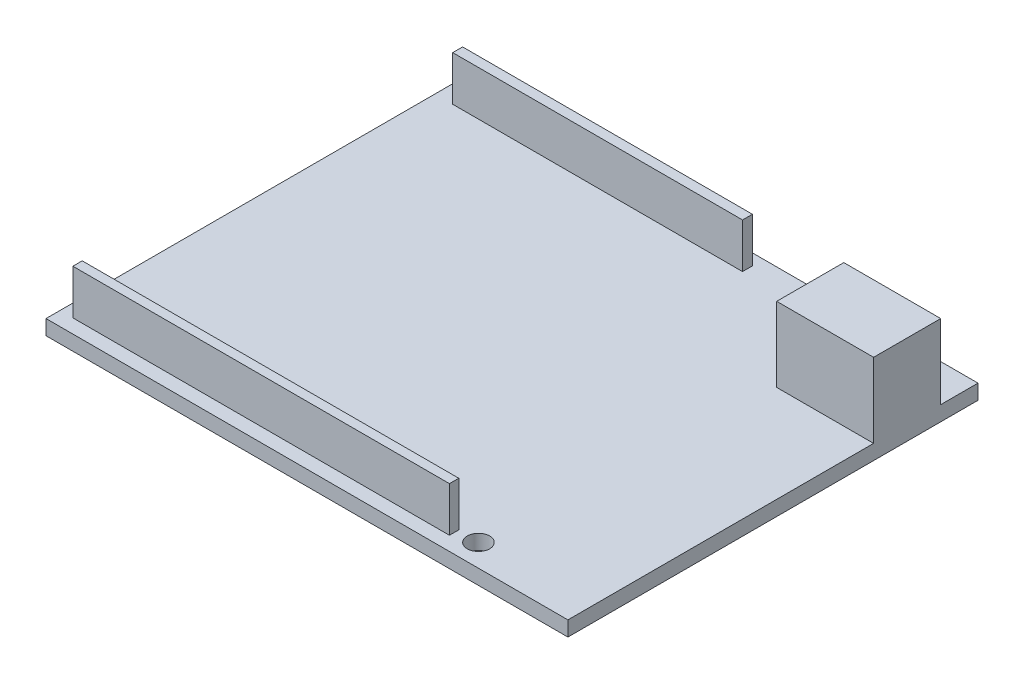
SolidWorks part; units mm, degrees
ref_plane "Plan de face" through (0, 0, 0) normal (0, 0, 1) x (1, 0, 0)
ref_plane "Plan de dessus" through (0, 0, 0) normal (0, 1, 0) x (1, 0, 0)
ref_plane "Plan de droite" through (0, 0, 0) normal (1, 0, 0) x (0, 0, -1)
sketch "Esquisse2" plane through (0, 0, 0) normal (0, 1, 0) x (1, 0, 0)
  line L1 (-35, 27.5) -> (35, 27.5)
  line L2 (-35, 27.5) -> (-35, -27.5)
  line L3 (-35, -27.5) -> (35, -27.5)
  line L4 (35, 27.5) -> (35, -27.5)
  line L5 (-35, 27.5) -> (35, -27.5) construction
  line L6 (-35, -27.5) -> (35, 27.5) construction
  point P0 (0, 0)
  dimension "D1" = 70
  dimension "D2" = 55
extrude "Boss.-Extru.1" add sketch "Esquisse2" along normal blind 2
sketch "Esquisse3" plane through (0, 2, 0) normal (0, 1, 0) x (1, 0, 0)
  line L0 (35, -27.5) -> (35, -12.5) construction
  line L1 (35, -27.5) -> (35, 27.5) construction
  line L2 (35, 27.5) -> (35, 22.5) construction
  line L4 (35, 22.5) -> (22, 22.5)
  line L5 (35, 22.5) -> (35, 13.5)
  line L6 (35, 13.5) -> (22, 13.5)
  line L7 (22, 22.5) -> (22, 13.5)
  dimension "D1" = 15
  dimension "D2" = 5
  dimension "D3" = 9
  dimension "D4" = 13
extrude "Boss.-Extru.2" add sketch "Esquisse3" along normal blind 10
sketch "Esquisse4" plane through (0, 2, 0) normal (0, 1, 0) x (1, 0, 0)
  line L1 (-32.6136, 25.9878) -> (6.2577, 25.9878)
  line L2 (-32.6136, 25.9878) -> (-32.6136, 24.6626)
  line L3 (-32.6136, 24.6626) -> (6.2577, 24.6626)
  line L4 (6.2577, 25.9878) -> (6.2577, 24.6626)
  line L5 (-33.2762, -24.3682) -> (17.227, -24.3682)
  line L6 (-33.2762, -24.3682) -> (-33.2762, -25.6197)
  line L7 (-33.2762, -25.6197) -> (17.227, -25.6197)
  line L8 (17.227, -24.3682) -> (17.227, -25.6197)
extrude "Boss.-Extru.3" add sketch "Esquisse4" along normal blind 6
sketch "Esquisse5" plane through (0, 2, 0) normal (0, 1, 0) x (1, 0, 0)
  line L0 (35, -27.5) -> (20, -27.5) construction
  line L1 (-35, -27.5) -> (35, -27.5) construction
  line L2 (20, -27.5) -> (20, -24.5) construction
  circle A0 centre (20, -24.5) radius 1.5
  dimension "D3" = 3
  dimension "D1" = 15
  dimension "D2" = 3
extrude "Enlèv. mat.-Extru.1" cut sketch "Esquisse5" against normal blind 6
sketch "Esquisse6" plane through (0, 2, 0) normal (0, 1, 0) x (1, 0, 0)
  line L0 (34.6749, 27.4602) -> (35, 27.5) construction
  line L1 (35, 27.5) -> (20.7, 27.5) construction
  line L2 (35, 27.5) -> (-35, 27.5) construction
  line L3 (20.7, 27.5) -> (20.7, 24.5) construction
  circle A0 centre (20.7, 24.5) radius 1.5
  dimension "D3" = 3
  dimension "D1" = 3
  dimension "D2" = 14.3
extrude "Enlèv. mat.-Extru.2" cut sketch "Esquisse6" against normal blind 6
